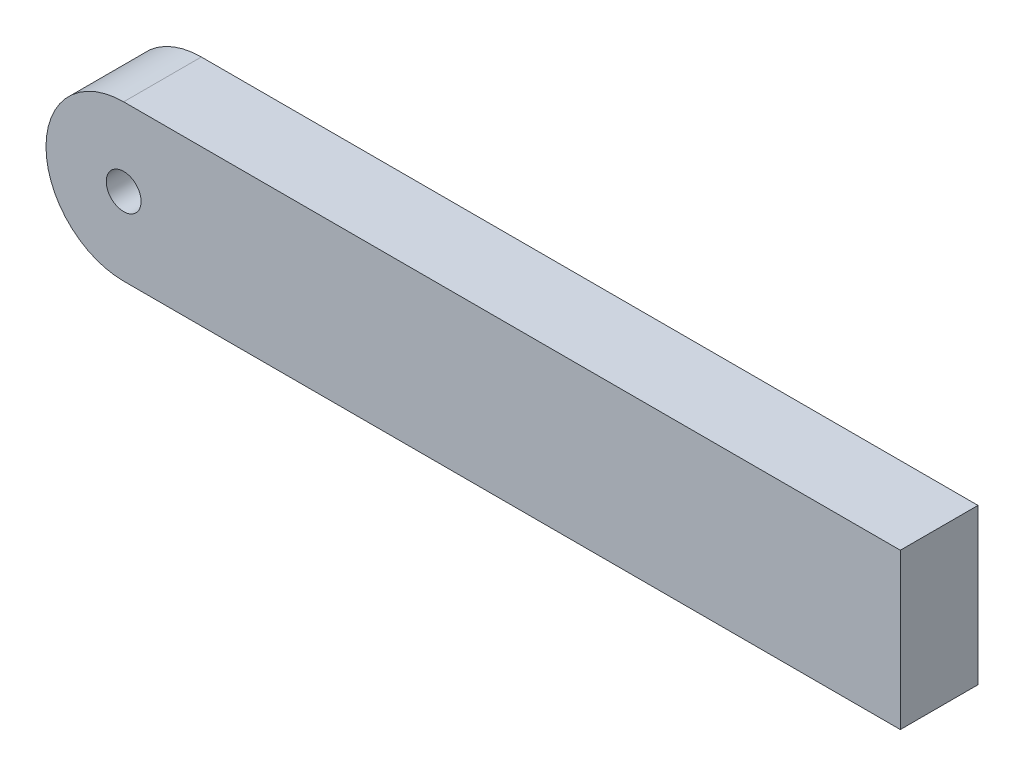
SolidWorks part; units mm, degrees
ref_plane "Front Plane" through (0, 0, 0) normal (0, 0, 1) x (1, 0, 0)
ref_plane "Top Plane" through (0, 0, 0) normal (0, 1, 0) x (1, 0, 0)
ref_plane "Right Plane" through (0, 0, 0) normal (1, 0, 0) x (0, 0, -1)
sketch "Sketch1" plane through (0, 0, 0) normal (0, 1, 0) x (1, 0, 0)
  line L0 (-10, 100) -> (10, 100) construction
  line L2 (10, -100) -> (10, 100)
  line L4 (-10, -100) -> (-10, 100)
  line L5 (10, -100) -> (-10, 100) construction
  line L6 (10, 100) -> (-10, -100) construction
  line L7 (-10, 0) -> (10, 0)
  line L8 (-1.5875, 98.4125) -> (1.5875, 98.4125)
  line L9 (-1.5875, 98.4125) -> (-1.5875, 101.5875)
  line L10 (-1.5875, 101.5875) -> (1.5875, 101.5875)
  line L11 (1.5875, 98.4125) -> (1.5875, 101.5875)
  line L12 (-1.5875, 98.4125) -> (1.5875, 101.5875) construction
  line L13 (-1.5875, 101.5875) -> (1.5875, 98.4125) construction
  arc A0 (-10, 100) -> (10, 100) centre (0, 100) cw
  arc A1 (10, -100) -> (-10, -100) centre (0, -100) cw
  circle A2 centre (0, -100) radius 2.5
  circle A3 centre (0, 100) radius 2.2451
  point P0 (0, 0)
  dimension "D3" = 5
  dimension "D1" = 200
  dimension "D2" = 20
  dimension "D4" = 3.175
extrude "Boss-Extrude1" add sketch "Sketch1" along normal blind 10 contours A1 L2 A0 L4 A3 A2
move or copy body "Body-Move/Copy1" bodies to move or copy 101 copy no rotation origin (-1.6667, 3.3333, -1.6667) rotation axis (0.5774, 0.5774, 0.5774) rotation angle 120
move or copy body "Body-Move/Copy2" bodies to move or copy 102 copy no translate (100, -5, 0)
